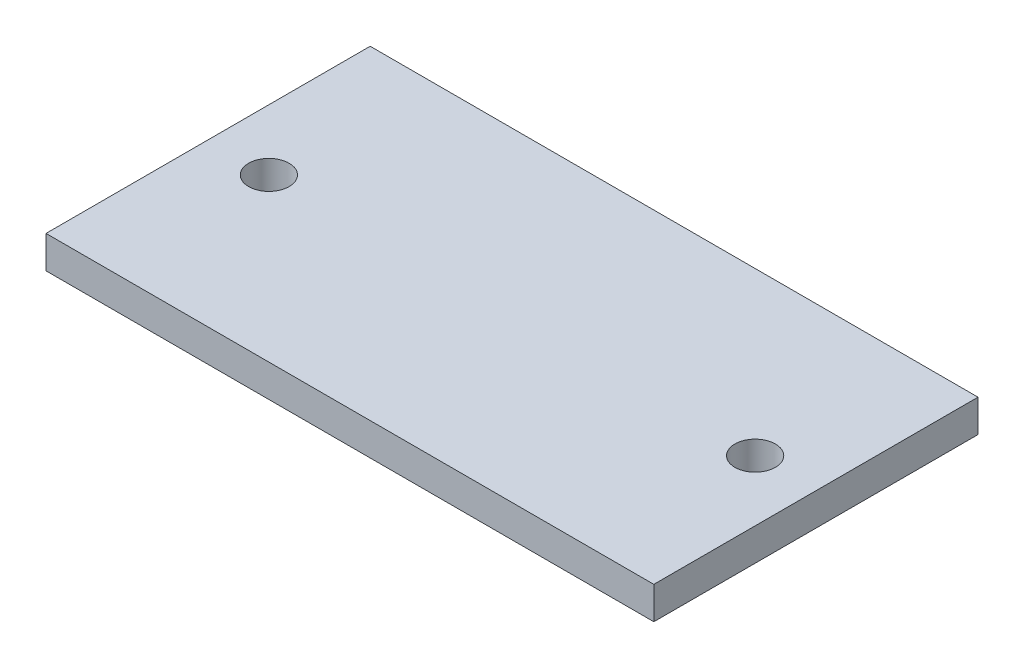
SolidWorks part; units mm, degrees
ref_plane "Ebene vorne" through (0, 0, 0) normal (0, 0, 1) x (1, 0, 0)
ref_plane "Ebene oben" through (0, 0, 0) normal (0, 1, 0) x (1, 0, 0)
ref_plane "Ebene rechts" through (0, 0, 0) normal (1, 0, 0) x (0, 0, -1)
sketch "Sketch1" plane through (0, 0, 0) normal (0, 1, 0) x (1, 0, 0)
  line L0 (-11.1, 5.1796) -> (-15, 5.1796) construction
  line L1 (0, 8) -> (-15, 8)
  line L2 (0, 8) -> (0, 0)
  line L3 (0, 0) -> (-15, 0)
  line L4 (-15, 8) -> (-15, 0)
  line L5 (-11.1, 9.5537) -> (-3.9, 9.5537) construction
  line L6 (-11.1, 9.5537) -> (-11.1, -1.1463) construction
  line L7 (-11.1, -1.1463) -> (-3.9, -1.1463) construction
  line L8 (-3.9, 9.5537) -> (-3.9, -1.1463) construction
  line L9 (-3.9, 5.1796) -> (0, 5.1796) construction
  dimension "D1" = 7.2
  dimension "D2" = 10.7
  dimension "D3" = 15
extrude "Boss-Extrude1" add sketch "Sketch1" along normal blind 0.8
sketch "Sketch4" plane through (0, 0.8, 0) normal (0, 1, 0) x (1, 0, 0)
  line L0 (-15, 8) -> (-15, 0) construction
  line L1 (0, 8) -> (0, 0) construction
  circle A0 centre (-13.5, 4) radius 0.5
  circle A1 centre (-1.5, 4) radius 0.5
  point P6 (-3.8239, 4)
  dimension "D1" = 1.5
  dimension "D2" = 1.5
extrude "Cut-Extrude1" cut sketch "Sketch4" against normal through all
